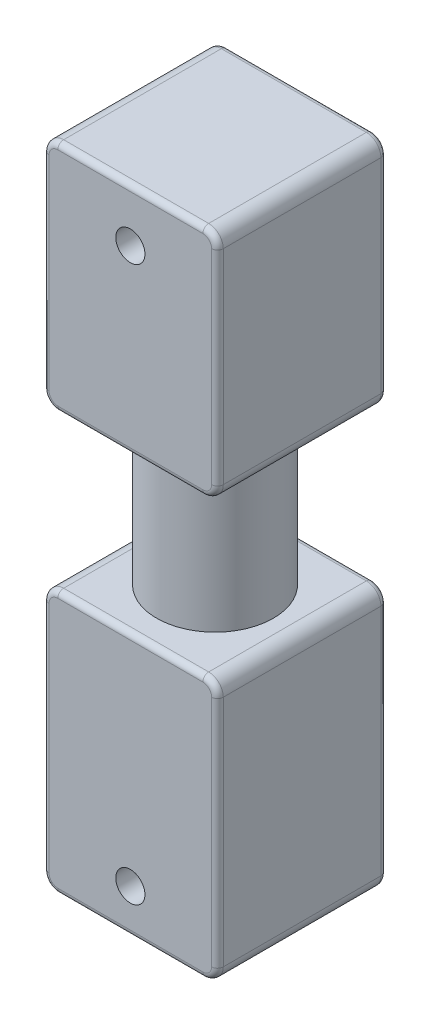
SolidWorks part; units mm, degrees
ref_plane "Front Plane" through (0, 0, 0) normal (0, 0, 1) x (1, 0, 0)
ref_plane "Top Plane" through (0, 0, 0) normal (0, 1, 0) x (1, 0, 0)
ref_plane "Right Plane" through (0, 0, 0) normal (1, 0, 0) x (0, 0, -1)
sketch "Sketch1" plane through (0, 0, 0) normal (0, 0, 1) x (1, 0, 0)
  line L0 (0, 0) -> (0, 106.5273) construction
  line L1 (-12.4188, 106.5273) -> (12.4188, 106.5273)
  line L2 (14.9188, 104.0273) -> (14.9188, 69.0273)
  line L3 (12.4188, 66.5273) -> (7.4188, 66.5273)
  line L5 (7.4188, 40) -> (12.4188, 40)
  line L6 (14.9188, 37.5) -> (14.9188, -2.5)
  line L8 (-14.9188, 37.5) -> (-14.9188, -2.5)
  line L9 (-7.4188, 40) -> (-12.4188, 40)
  line L10 (-12.4188, 66.5273) -> (-7.4188, 66.5273)
  line L11 (-14.9188, 104.0273) -> (-14.9188, 69.0273)
  line L12 (-7.4188, 40) -> (7.4188, 40)
  line L13 (-7.4188, 66.5273) -> (7.4188, 66.5273)
  line L15 (-12.4188, -5) -> (12.4188, -5)
  arc A0 (12.4188, 106.5273) -> (14.9188, 104.0273) centre (12.4188, 104.0273) cw
  arc A1 (14.9188, 69.0273) -> (12.4188, 66.5273) centre (12.4188, 69.0273) cw
  arc A3 (14.9188, 37.5) -> (12.4188, 40) centre (12.4188, 37.5) ccw
  arc A7 (-14.9188, 37.5) -> (-12.4188, 40) centre (-12.4188, 37.5) cw
  arc A8 (-14.9188, 69.0273) -> (-12.4188, 66.5273) centre (-12.4188, 69.0273) ccw
  arc A9 (-12.4188, 106.5273) -> (-14.9188, 104.0273) centre (-12.4188, 104.0273) ccw
  arc A10 (-14.9188, -2.5) -> (-12.4188, -5) centre (-12.4188, -2.5) ccw
  arc A11 (14.9188, -2.5) -> (12.4188, -5) centre (12.4188, -2.5) cw
  point P10 (-14.9188, -5)
  point P34 (14.9188, -5)
  point P35 (0, -5)
  dimension "D3" = 2.5
  dimension "D4" = 2.5
  dimension "D5" = 2.5
  dimension "D6" = 2.5
  dimension "D1" = 2.5
  dimension "D2" = 40
extrude "Boss-Extrude1" add sketch "Sketch1" along normal blind 29
fillet "Fillet1" radius 1 16 edges at (-14.9188, 17.5, 29) (-14.1866, 39.2678, 29) (0, 40, 29) (14.1866, 39.2678, 29) (-14.9188, 17.5, 0) (-14.1866, 39.2678, 0) (0, 40, 0) (14.1866, 39.2678, 0) (14.9188, 17.5, 29) (14.9188, 17.5, 0) (14.1866, -4.2678, 29) (0, -5, 29) (-14.1866, -4.2678, 29) (14.1866, -4.2678, 0) (0, -5, 0) (-14.1866, -4.2678, 0)
fillet "Fillet2" radius 1 16 edges at (14.1866, 105.7951, 29) (14.9188, 86.5273, 29) (14.1866, 67.2595, 29) (0, 66.5273, 29) (-14.1866, 67.2595, 29) (-14.9188, 86.5273, 29) (-14.1866, 105.7951, 29) (14.1866, 105.7951, 0) (14.9188, 86.5273, 0) (14.1866, 67.2595, 0) (0, 66.5273, 0) (-14.1866, 67.2595, 0) (-14.9188, 86.5273, 0) (-14.1866, 105.7951, 0) (0, 106.5273, 29) (0, 106.5273, 0)
sketch "Sketch3" plane through (0, 40, 0) normal (0, 1, 0) x (1, 0, 0)
  line L0 (0, -1) -> (0, -28) construction
  line L1 (12.4188, -1) -> (-12.4188, -1) construction
  line L2 (-12.4188, -28) -> (12.4188, -28) construction
  circle A0 centre (0, -14.5) radius 10
extrude "Boss-Extrude2" add sketch "Sketch3" along normal up to surface (26.5273 mm away) up to face at (0, 66.5273, 14.5)
sketch "Sketch4" plane through (0, 0, 0) normal (0, 0, -1) x (-1, 0, 0)
  line L0 (0, 106.5273) -> (0, 0) construction
  line L1 (-12.4188, 106.5273) -> (12.4188, 106.5273) construction
  line L2 (0, 53.2637) -> (26.3931, 53.2637) construction
  line L4 (26.3931, 2.5) -> (0, 2.5) construction
  line L5 (26.3931, 97.5) -> (0, 97.5) construction
  circle A0 centre (0, 97.5) radius 2.5
  circle A1 centre (0, 2.5) radius 2.5
  point P10 (26.3931, 53.2637)
extrude "Cut-Extrude4" cut sketch "Sketch4" against normal through all
